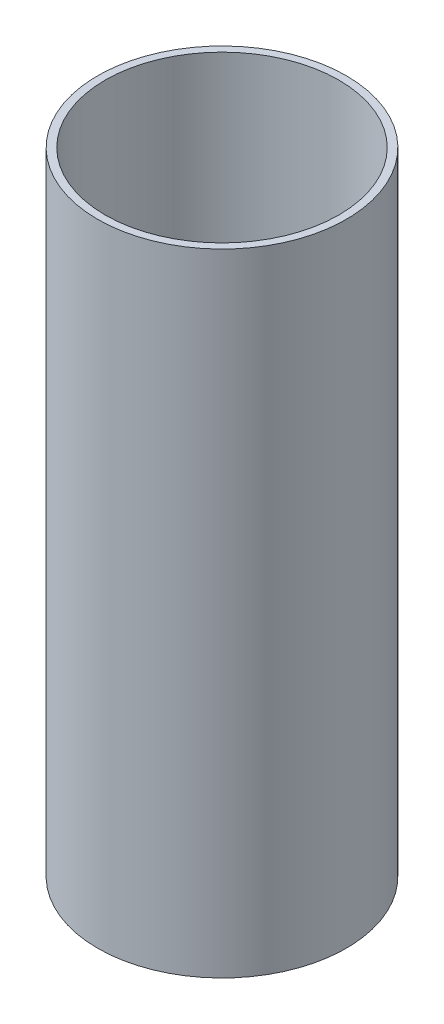
SolidWorks part; units mm, degrees
ref_plane "Front Plane" through (0, 0, 0) normal (0, 0, 1) x (1, 0, 0)
ref_plane "Top Plane" through (0, 0, 0) normal (0, 1, 0) x (1, 0, 0)
ref_plane "Right Plane" through (0, 0, 0) normal (1, 0, 0) x (0, 0, -1)
sketch "Sketch1" plane through (0, 0, 0) normal (0, 1, 0) x (1, 0, 0)
  circle A0 centre (0, 0) radius 33.1
  dimension "D1" = 66.2
extrude "Boss-Extrude1" add sketch "Sketch1" along normal blind 168 contours A0
shell "Shell1" thickness 2
sketch "Sketch2" plane through (0, 168, 0) normal (0, 1, 0) x (1, 0, 0)
  circle A0 centre (0, 0) radius 31.1 construction
  circle A1 centre (0, 0) radius 31.1
extrude "Cut-Extrude1" cut sketch "Sketch2" against normal blind 38
